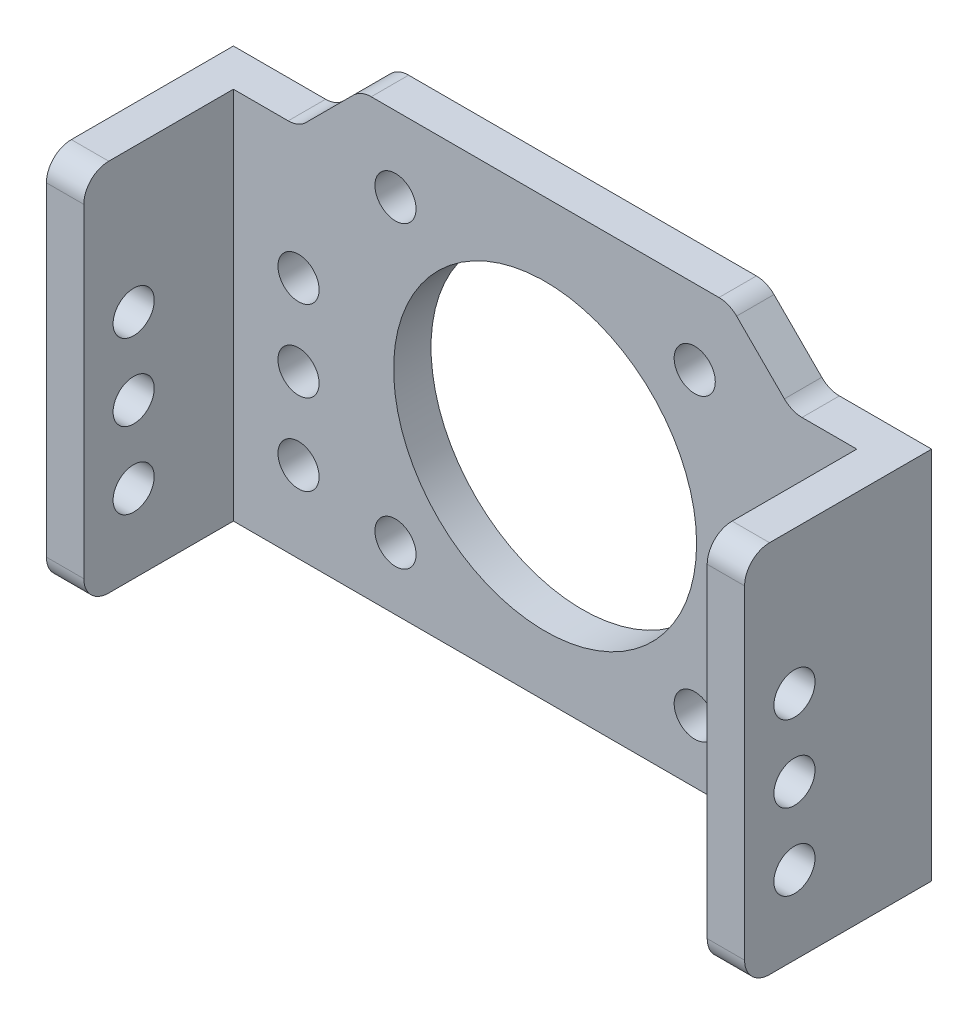
SolidWorks part; units mm, degrees
ref_plane "前视基准面" through (0, 0, 0) normal (0, 0, 1) x (1, 0, 0)
ref_plane "上视基准面" through (0, 0, 0) normal (0, 1, 0) x (1, 0, 0)
ref_plane "右视基准面" through (0, 0, 0) normal (1, 0, 0) x (0, 0, -1)
sketch "草图1" plane through (0, 0, 0) normal (0, 0, 1) x (1, 0, 0)
  line L1 (0, 0) -> (56, 0)
  line L2 (0, 0) -> (0, 30)
  line L3 (0, 30) -> (56, 30)
  line L4 (56, 0) -> (56, 30)
  line L6 (40, 13) -> (40, 5)
  line L12 (8.2237, 30) -> (13.2261, 35.0024)
  line L13 (47.7763, 30) -> (42.7739, 35.0024)
  line L14 (42.7739, 35.0024) -> (13.2261, 35.0024)
  circle A0 centre (28, 17) radius 12.15
  circle A1 centre (8.2237, 13) radius 1.65
  circle A2 centre (47.7763, 13) radius 1.65
  circle A3 centre (16, 5) radius 1.65
  circle A4 centre (40, 5) radius 1.65
  circle A5 centre (40, 29) radius 1.65
  circle A6 centre (16, 29) radius 1.65
  circle A7 centre (47.7763, 19.5) radius 1.65
  circle A8 centre (47.7763, 6.5) radius 1.65
  circle A9 centre (8.2237, 19.5) radius 1.65
  circle A10 centre (8.2237, 6.5) radius 1.65
extrude "凸台-拉伸6" add sketch "草图1" along normal blind 3
sketch "草图4" plane through (0, 0, 3) normal (0, 0, 1) x (1, 0, 0)
  line L0 (0, 30) -> (3, 30)
  line L1 (0, 30) -> (0, -8)
  line L2 (3, 30) -> (3, -8)
  line L3 (0, -8) -> (3, -8)
  line L4 (0, 30) -> (8.2237, 30) construction
  line L5 (0, 0) -> (56, 0) construction
  line L6 (56, 30) -> (53, 30)
  line L7 (56, 30) -> (56, -8)
  line L8 (53, 30) -> (53, -8)
  line L9 (56, -8) -> (53, -8)
  line L10 (47.7763, 30) -> (56, 30) construction
  line L11 (0, 0) -> (56, 0)
  point P7 (4.1118, 30)
  line M15 (0, 0) -> (56, 0)
  line M16 (56, 0) -> (56, 30)
  line M17 (56, 30) -> (47.7763, 30)
  line M21 (8.2237, 30) -> (0, 30)
  line M22 (0, 30) -> (0, 0)
  dimension "D1" = 30
extrude "凸台-拉伸7" add sketch "草图4" along normal blind 12 contours L2 M21 M22 M15 | L8 M17 M15 M16
sketch "草图5" plane through (56, 0, 0) normal (1, 0, 0) x (0, 0, -1)
  line L0 (-3, 30) -> (-15, 30)
  line L1 (-15, 30) -> (-15, 0)
  line L2 (-15, 0) -> (-3, 0)
  line L3 (-3, 30) -> (-3, 0)
  line L4 (-11, 12.4) -> (-5.1431, 12.4)
  line L6 (-11, 0) -> (-11, 6.275)
  line L7 (-11, 6.275) -> (-11, 12.4)
  line L8 (-15, 0) -> (0, 0) construction
  circle A1 centre (-11, 6.275) radius 1.65
  circle A2 centre (-11, 12.4) radius 1.65
  circle A3 centre (-11, 18.525) radius 1.65
extrude "切除-拉伸1" cut sketch "草图5" against normal blind 56 contours A3 | L4 A2 L7 | L7 A2 L4 | L7 A1 L6 | L6 A1 L7
fillet "圆角6" radius 2 8 edges at (8.2237, 30, 1.5) (13.2261, 35.0024, 1.5) (47.7763, 30, 1.5) (42.7739, 35.0024, 1.5) (54.5, 0, 15) (54.5, 30, 15) (1.5, 0, 15) (1.5, 30, 15)
